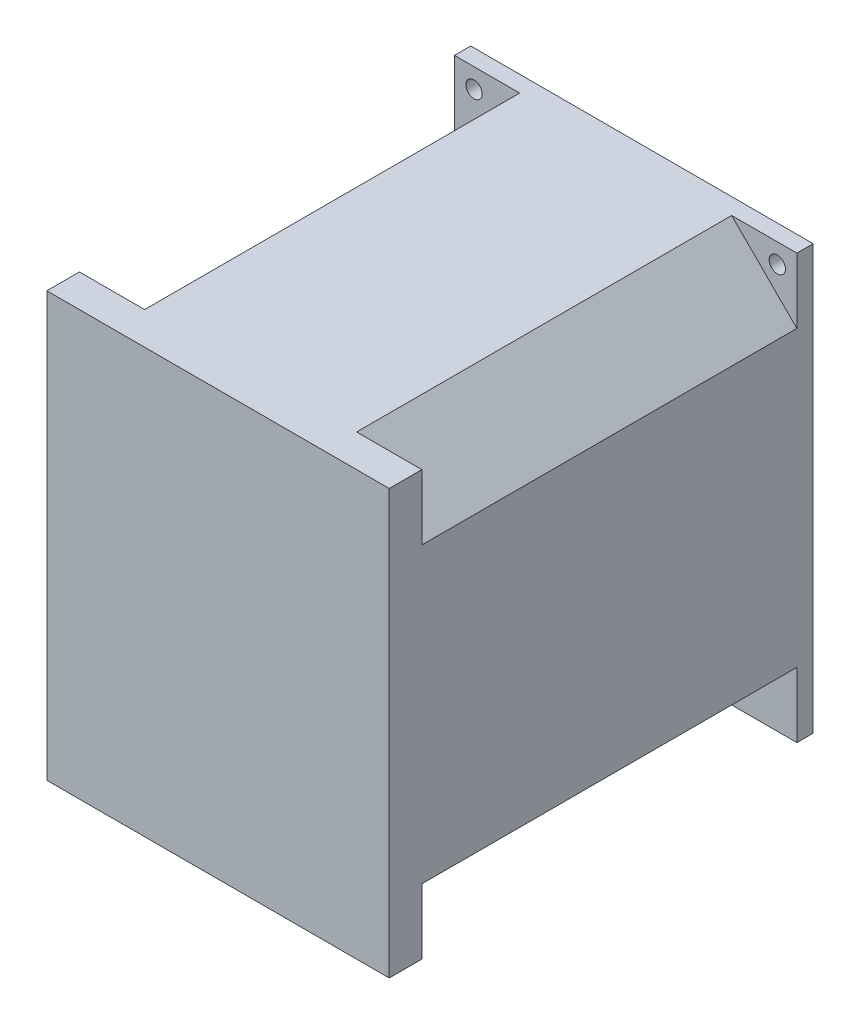
SolidWorks part; units mm, degrees
material "PW80:Md:De:1:18:"
ref_plane "Plan1" through (0, 0, 0) normal (0, 0, 1) x (1, 0, 0)
ref_plane "Plan2" through (0, 0, 0) normal (0, 1, 0) x (1, 0, 0)
ref_plane "Plan3" through (0, 0, 0) normal (1, 0, 0) x (0, 0, -1)
sketch "Esquisse1" plane through (0, 0, 0) normal (1, 0, 0) x (0, 0, -1)
  line L1 (0, 0) -> (130, 0)
  line L2 (0, 0) -> (0, 130)
  line L3 (0, 130) -> (130, 130)
  line L4 (130, 0) -> (130, 130)
extrude "Base-Extrusion" add sketch "Esquisse1" along normal blind 105
ref_plane "Plan4" through (0, 0, -10) normal (0, 0, 1) x (1, 0, 0)
sketch "Esquisse3" plane through (0, 0, -10) normal (0, 0, 1) x (1, 0, 0)
  line L0 (0, 0) -> (20, 0)
  line L1 (105, 0) -> (0, 0) construction
  line L2 (20, 0) -> (0, 20)
  line L3 (0, 130) -> (0, 0) construction
  line L4 (0, 20) -> (0, 0)
  line L5 (0, 130) -> (0, 110)
  line L6 (0, 110) -> (20, 130)
  line L7 (20, 130) -> (0, 130)
  line L8 (105, 130) -> (105, 110)
  line L9 (105, 130) -> (105, 0) construction
  line L10 (105, 110) -> (85, 130)
  line L11 (105, 130) -> (0, 130) construction
  line L12 (85, 130) -> (105, 130)
  line L13 (105, 0) -> (105, 20)
  line L14 (105, 20) -> (85, 0)
  line L15 (85, 0) -> (105, 0)
extrude "Enlèv. mat.-Extru.1" cut sketch "Esquisse3" against normal blind 115
sketch "Esquisse4" plane through (0, 0, -130) normal (0, 0, -1) x (-1, 0, 0)
  circle A0 centre (-6, 124) radius 2.5
  circle A1 centre (-99, 124) radius 2.5
extrude "Enlèv. mat.-Extru.2" cut sketch "Esquisse4" against normal blind 5
